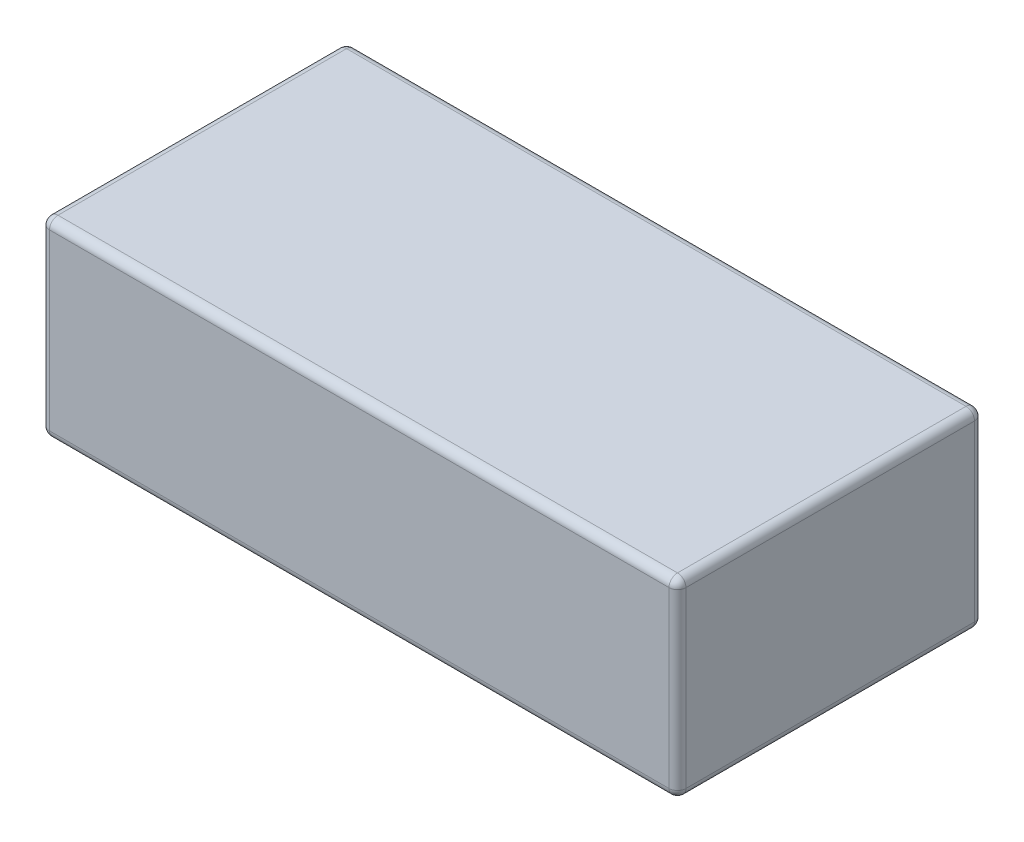
SolidWorks part; units mm, degrees
ref_plane "Front Plane" through (0, 0, 0) normal (0, 0, 1) x (1, 0, 0)
ref_plane "Top Plane" through (0, 0, 0) normal (0, 1, 0) x (1, 0, 0)
ref_plane "Right Plane" through (0, 0, 0) normal (1, 0, 0) x (0, 0, -1)
sketch "Sketch1" plane through (0, 0, 0) normal (0, 1, 0) x (1, 0, 0)
  line L1 (-75, -36) -> (75, -36)
  line L2 (-75, -36) -> (-75, 36)
  line L3 (-75, 36) -> (75, 36)
  line L4 (75, -36) -> (75, 36)
  line L5 (-75, -36) -> (75, 36) construction
  line L6 (-75, 36) -> (75, -36) construction
  point P0 (0, 0)
  dimension "D1" = 150
  dimension "D2" = 72
extrude "Boss-Extrude1" add sketch "Sketch1" along normal blind 45
fillet "Fillet1" radius 2 12 edges at (75, 45, 0) (0, 45, -36) (-75, 45, 0) (0, 45, 36) (-75, 22.5, -36) (-75, 0, 0) (0, 0, -36) (75, 22.5, -36) (75, 0, 0) (75, 22.5, 36) (-75, 22.5, 36) (0, 0, 36)
